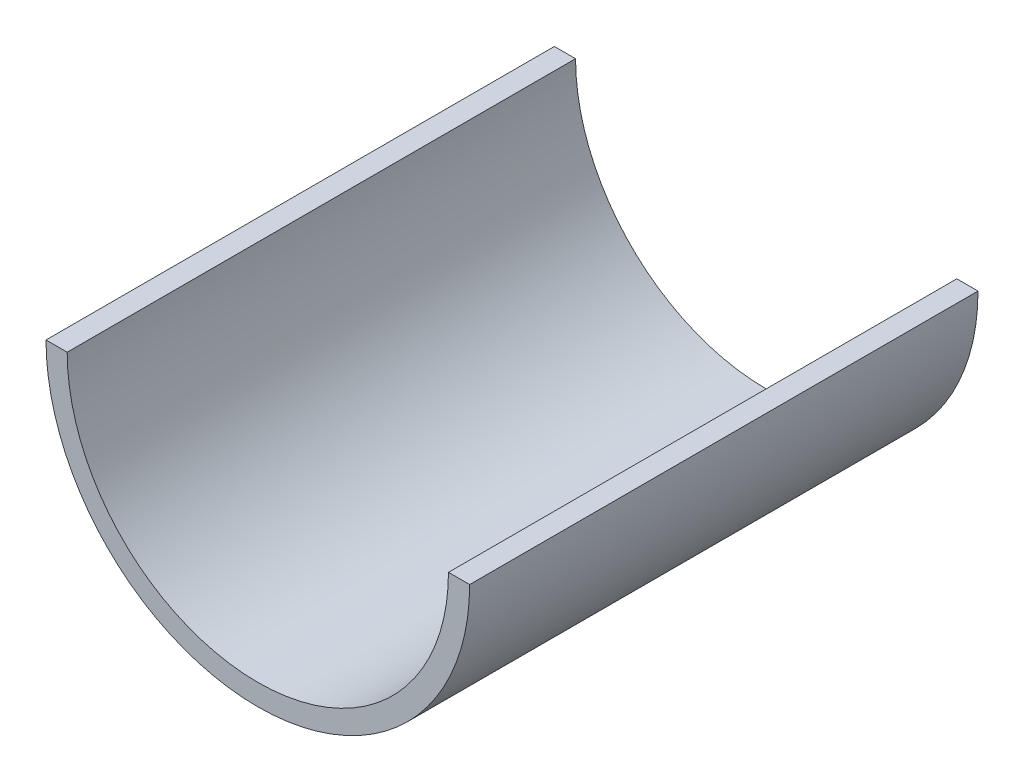
SolidWorks part; units mm, degrees
ref_plane "Front" through (0, 0, 0) normal (0, 0, 1) x (1, 0, 0)
ref_plane "Top" through (0, 0, 0) normal (0, 1, 0) x (1, 0, 0)
ref_plane "Right" through (0, 0, 0) normal (1, 0, 0) x (0, 0, -1)
sketch "Sketch1" plane through (0, 0, 0) normal (0, 0, 1) x (1, 0, 0)
  line L0 (63.5, 0) -> (-63.5, 0) construction
  line L1 (-63.5, 0) -> (-57.15, 0)
  line L2 (57.15, 0) -> (63.5, 0)
  arc A0 (-63.5, 0) -> (63.5, 0) centre (0, 0) ccw
  arc A1 (-57.15, 0) -> (57.15, 0) centre (0, 0) ccw
  point P6 (0, 0)
  dimension "D1" = 127
  dimension "D2" = 114.3
extrude "Boss-Extrude1" add sketch "Sketch1" along normal blind 152.4
